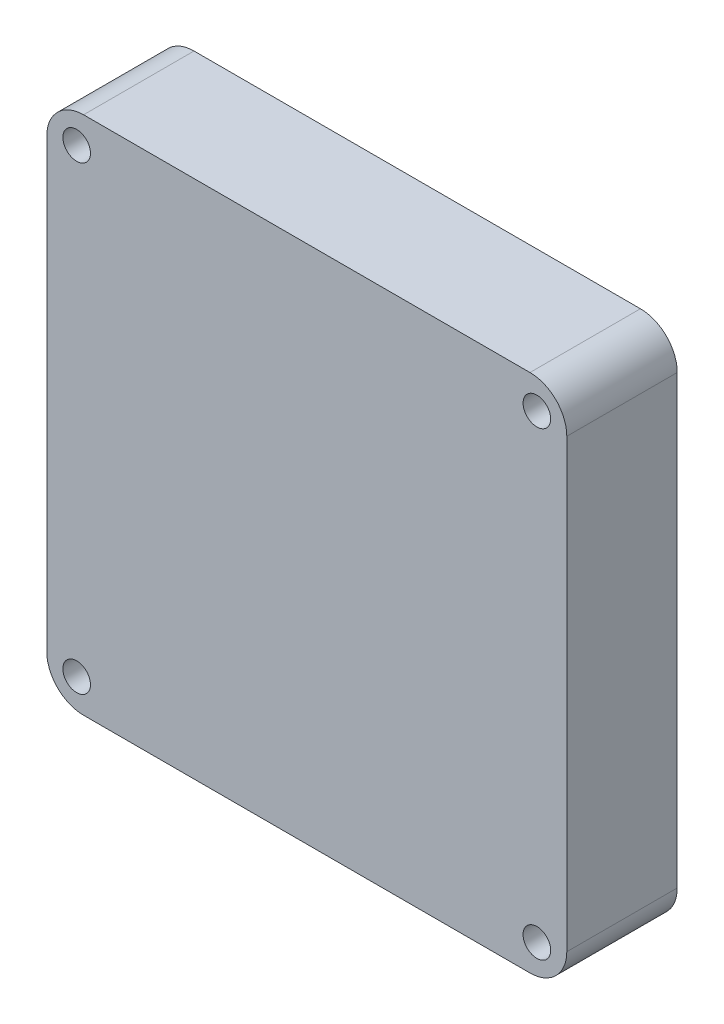
SolidWorks part; units mm, degrees
ref_plane "Спереди" through (0, 0, 0) normal (0, 0, 1) x (1, 0, 0)
ref_plane "Сверху" through (0, 0, 0) normal (0, 1, 0) x (1, 0, 0)
ref_plane "Справа" through (0, 0, 0) normal (1, 0, 0) x (0, 0, -1)
sketch "Эскиз1" plane through (0, 0, 0) normal (0, 0, 1) x (1, 0, 0)
  line L1 (-28.25, 28.25) -> (28.25, 28.25)
  line L2 (-28.25, 28.25) -> (-28.25, -28.25)
  line L3 (-28.25, -28.25) -> (28.25, -28.25)
  line L4 (28.25, 28.25) -> (28.25, -28.25)
  line L5 (-28.25, 28.25) -> (28.25, -28.25) construction
  line L6 (-28.25, -28.25) -> (28.25, 28.25) construction
  line L7 (-25, 25) -> (25, 25) construction
  line L8 (-25, 25) -> (-25, -25) construction
  line L9 (-25, -25) -> (25, -25) construction
  line L10 (25, 25) -> (25, -25) construction
  line L11 (-25, 25) -> (25, -25) construction
  line L12 (-25, -25) -> (25, 25) construction
  circle A0 centre (-25, 25) radius 1.5
  circle A1 centre (25, 25) radius 1.5
  circle A2 centre (25, -25) radius 1.5
  circle A3 centre (-25, -25) radius 1.5
  point P0 (0, 0)
  point P5 (0, 0)
  point P20 (0, 0)
  dimension "D3" = 4
  dimension "D4" = 3
  dimension "D1" = 50
  dimension "D2" = 56.5
extrude "Плата" add sketch "Эскиз1" along normal blind 12
fillet "Скругление1" radius 4 4 edges at (-28.25, -28.25, 6) (-28.25, 28.25, 6) (28.25, -28.25, 6) (28.25, 28.25, 6)
